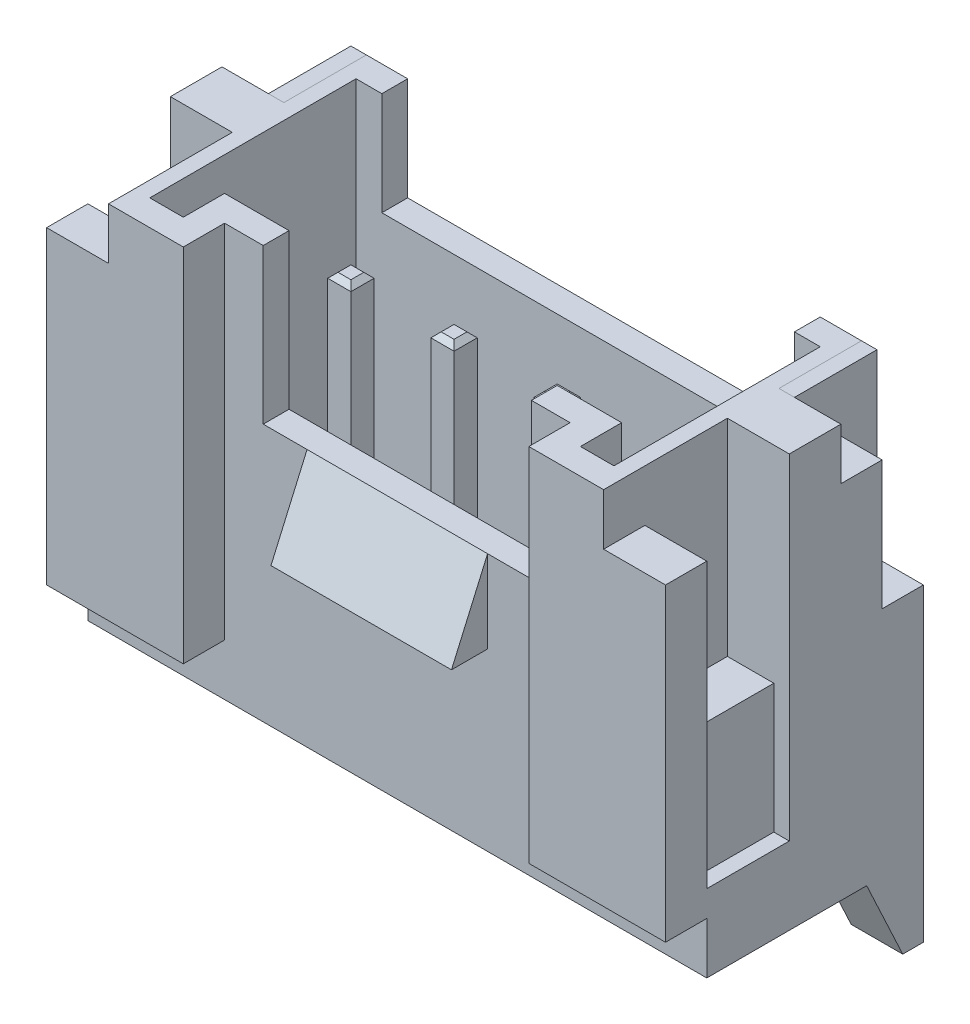
SolidWorks part; units mm, degrees
ref_plane "Plan de face" through (0, 0, 0) normal (0, 0, 1) x (1, 0, 0)
ref_plane "Plan de dessus" through (0, 0, 0) normal (0, 1, 0) x (1, 0, 0)
ref_plane "Plan de droite" through (0, 0, 0) normal (1, 0, 0) x (0, 0, -1)
sketch "Esquisse1" plane through (0, 0, 0) normal (1, 0, 0) x (0, 0, -1)
  line L0 (0, 0) -> (-5, 0)
  line L1 (-5, 0) -> (-5, -7)
  line L2 (-5, -7) -> (-4.2, -7)
  line L3 (-4.2, -7) -> (-4.2, -8)
  line L4 (-4.2, -8) -> (0, -8)
  line L7 (0, -8) -> (0, 0)
  dimension "D1" = 5
  dimension "D2" = 0.8
  dimension "D3" = 1
  dimension "D4" = 8
extrude "Boss.-Extru.1" add sketch "Esquisse1" along normal mid plane 12
sketch "Esquisse2" plane through (0, 0, 0) normal (1, 0, 0) x (0, 0, -1)
  line L0 (0, -8) -> (0, -9.5)
  line L1 (0, -9.5) -> (-0.4, -9.5)
  line L2 (-0.4, -9.5) -> (-1.0995, -8)
  line L3 (-4.2, -8) -> (0, -8) construction
  line L4 (-1.0995, -8) -> (0, -8)
  dimension "D1" = 1.5
  dimension "D2" = 0.4
  dimension "D3" = 25
extrude "Boss.-Extru.2" add sketch "Esquisse2" along normal blind 1 from offset 5
sketch "Esquisse3" plane through (0, 0, 0) normal (0, 1, 0) x (1, 0, 0)
  line L0 (6, -5) -> (-6, -5) construction
  line L1 (3.35, -5.8) -> (-3.35, -5.8)
  line L2 (3.35, -5.8) -> (3.35, -4.2)
  line L3 (3.35, -4.2) -> (-3.35, -4.2)
  line L4 (-3.35, -5.8) -> (-3.35, -4.2)
  line L5 (3.35, -5.8) -> (-3.35, -4.2) construction
  line L6 (3.35, -4.2) -> (-3.35, -5.8) construction
  point P0 (0, -5)
  dimension "D1" = 6.7
  dimension "D2" = 0.8
extrude "Enlèv. mat.-Extru.1" cut sketch "Esquisse3" against normal through all
sketch "Esquisse4" plane through (0, 0, 0) normal (0, 1, 0) x (1, 0, 0)
  line L8 (-6, 0) -> (-6, -5) construction
  line L9 (6, 0) -> (6, -5) construction
  line L16 (-5.5, -4.5) -> (-3.85, -4.5)
  line L17 (-3.85, -4.5) -> (-3.85, -3.7)
  line L18 (-3.85, -3.7) -> (3.85, -3.7)
  line L19 (3.85, -3.7) -> (3.85, -4.5)
  line L20 (3.85, -4.5) -> (5.5, -4.5)
  line L21 (5.5, -4.5) -> (5.5, -0.5)
  line L22 (5.5, -0.5) -> (-5.5, -0.5)
  line L23 (-5.5, -0.5) -> (-5.5, -4.5)
  line L24 (-4.5, -4.5) -> (-3.85, -4.5)
  line L25 (-3.85, -4.5) -> (-3.85, -3.7)
  line L26 (-3.85, -3.7) -> (3.85, -3.7)
  line L27 (3.85, -3.7) -> (3.85, -4.5)
  line L28 (3.85, -4.5) -> (4.5, -4.5)
  line L29 (4.5, -4.5) -> (4.5, -0.5)
  line L30 (4.5, -0.5) -> (-4.5, -0.5)
  line L31 (-4.5, -0.5) -> (-4.5, -4.5)
  dimension "D2" = 1.5
  dimension "D3" = 1.5
  dimension "D1" = 0.5
extrude "Enlèv. mat.-Extru.2" cut sketch "Esquisse4" against normal blind 6.5
sketch "Esquisse7" plane through (6, 0, 0) normal (1, 0, 0) x (0, 0, -1)
  line L0 (-5, -1) -> (-4.2, -1)
  line L1 (-5, 0) -> (-5, -7) construction
  line L2 (-4.2, -1) -> (-4.2, -4)
  line L3 (-4.2, -4) -> (-2.6, -4)
  line L4 (-2.6, -4) -> (-2.6, 0)
  line L5 (0, 0) -> (-5, 0) construction
  line L6 (-2.6, 0) -> (-5, 0)
  line L7 (-5, 0) -> (-5, -1)
  line L8 (0, 0) -> (-1.6, 0)
  line L9 (-1.6, 0) -> (-1.6, -1)
  line L10 (-1.6, -1) -> (-0.8, -1)
  line L11 (-0.8, -1) -> (-0.8, -3.5)
  line L12 (-0.8, -3.5) -> (0, -3.5)
  line L13 (0, -9.5) -> (0, 0) construction
  line L14 (0, -3.5) -> (0, 0)
  dimension "D1" = 1
  dimension "D2" = 2.4
  dimension "D3" = 1.6
  dimension "D4" = 4
  dimension "D5" = 1
  dimension "D6" = 1.8
  dimension "D7" = 3.5
extrude "Enlèv. mat.-Extru.4" cut sketch "Esquisse7" against normal blind 1.2
sketch "Esquisse8" plane through (6, 0, 0) normal (1, 0, 0) x (0, 0, -1)
  line L0 (-2.6, -4) -> (-2.6, 0) construction
  line L1 (-4.2, -4) -> (-2.6, -4)
  line L2 (-4.2, -4) -> (-4.2, -6.5)
  line L3 (-4.2, -6.5) -> (-2.6, -6.5)
  line L4 (-2.6, -4) -> (-2.6, -6.5)
  line L5 (-5, -7) -> (-4.2, -7) construction
  dimension "D1" = 0.5
extrude "Enlèv. mat.-Extru.5" cut sketch "Esquisse8" against normal blind 0.3
sketch "Esquisse9" plane through (0, 0, 0.5) normal (0, 0, 1) x (1, 0, 0)
  line L1 (-2.8, 1) -> (2.8, 1)
  line L2 (-2.8, 1) -> (-2.8, -1)
  line L3 (-2.8, -1) -> (2.8, -1)
  line L4 (2.8, 1) -> (2.8, -1)
  line L5 (-2.8, 1) -> (2.8, -1) construction
  line L6 (-2.8, -1) -> (2.8, 1) construction
  line L7 (4.5, 0) -> (-4.5, 0) construction
  line L8 (4.8, -3.5) -> (4.8, 0) construction
  dimension "D1" = 1
  dimension "D2" = 2
extrude "Enlèv. mat.-Extru.6" cut sketch "Esquisse9" against normal through all
sketch "Esquisse10" plane through (0, 0, 4.2) normal (0, 0, 1) x (1, 0, 0)
  line L1 (-2.6, 3) -> (2.6, 3)
  line L2 (-2.6, 3) -> (-2.6, -3)
  line L3 (-2.6, -3) -> (2.6, -3)
  line L4 (2.6, 3) -> (2.6, -3)
  line L5 (-2.6, 3) -> (2.6, -3) construction
  line L6 (-2.6, -3) -> (2.6, 3) construction
  line L7 (3.35, 0) -> (-3.35, 0) construction
  line L8 (4.8, 0) -> (4.8, -1) construction
  dimension "D1" = 3
  dimension "D2" = 2.2
extrude "Enlèv. mat.-Extru.7" cut sketch "Esquisse10" against normal up to next
sketch "Esquisse12" plane through (0, 0, 0) normal (1, 0, 0) x (0, 0, -1)
  line L0 (-4.2, -3) -> (-4.9, -4.6)
  line L1 (-4.9, -4.6) -> (-4.2, -4.6)
  line L2 (-4.2, -4.6) -> (-4.2, -3)
  dimension "D1" = 0.7
  dimension "D2" = 1.6
extrude "Boss.-Extru.3" add sketch "Esquisse12" along normal mid plane 3.5
sketch "Esquisse5" plane through (0, 0, 0) normal (0, 1, 0) x (1, 0, 0)
  line L0 (4.5, -0.5) -> (2.8, -0.5) construction
  line L1 (4, 0.5) -> (-4, 0.5)
  line L2 (4, 0.5) -> (4, -0.5)
  line L3 (4, -0.5) -> (-4, -0.5)
  line L4 (-4, 0.5) -> (-4, -0.5)
  line L5 (4, 0.5) -> (-4, -0.5) construction
  line L6 (4, -0.5) -> (-4, 0.5) construction
  line L7 (6, -1.6) -> (6, -2.6) construction
  point P0 (0, 0)
  dimension "D1" = 2
extrude "Enlèv. mat.-Extru.3" cut sketch "Esquisse5" against normal blind 2
sketch "Esquisse13" plane through (0, 0, 0) normal (1, 0, 0) x (0, 0, -1)
  line L0 (-2.1, -1.7) -> (-2.1, -8)
  line L1 (-1.85, -8.25) -> (-0.5, -8.25)
  line L2 (-0.25, -8.5) -> (-0.25, -10)
  line L3 (0, -9.5) -> (0, -3.5) construction
  line L4 (-4.2, -8) -> (-1.0995, -8) construction
  arc A0 (-1.85, -8.25) -> (-2.1, -8) centre (-1.85, -8) cw
  arc A1 (-0.5, -8.25) -> (-0.25, -8.5) centre (-0.5, -8.5) cw
  dimension "D1" = 0.25
  dimension "D2" = 0.25
  dimension "D3" = 0.25
  dimension "D4" = 6.3
  dimension "D5" = 2
  dimension "D6" = 2.1
extrude "Extru.-Mince1" add sketch "Esquisse13" along normal mid plane 0.45 from offset 3 separate body thin thin type mid plane wall 0.45
chamfer "Chanfrein1" distance 0.1 angle 45 4 edges at (3, -1.7, 1.875) (3.225, -1.7, 2.1) (3, -1.7, 2.325) (2.775, -1.7, 2.1)
chamfer "Chanfrein2" distance 0.6 distance2 0.3 1 edges at (3, -10, 0.475)
pattern_linear "Répétition linéaire1" count 4 spacing 2 along (-1, 0, 0) of "Extru.-Mince1", "Chanfrein2", "Chanfrein1"
sketch "Esquisse14" plane through (4.8, 0, 0) normal (1, 0, 0) x (0, 0, -1)
  line L6 (0, -3.5) -> (0, 0)
  line L7 (0, 0) -> (-1.6, 0)
  line L8 (-1.6, 0) -> (-1.6, -1)
  line L9 (-1.6, -1) -> (-0.8, -1)
  line L10 (-0.8, -1) -> (-0.8, -3.5)
  line L11 (-0.8, -3.5) -> (0, -3.5)
  line L12 (0, -3.5) -> (0, 0)
  line L13 (0, 0) -> (-1.6, 0)
  line L14 (-1.6, 0) -> (-1.6, -1)
  line L15 (-1.6, -1) -> (-0.8, -1)
  line L16 (-0.8, -1) -> (-0.8, -3.5)
  line L17 (-0.8, -3.5) -> (0, -3.5)
  dimension "D1" = 0
extrude "Boss.-Extru.4" add sketch "Esquisse14" along normal blind 0.3 separate body
mirror "Symétrie2" about plane through (0, 0, 0) normal (1, 0, 0) of "Enlèv. mat.-Extru.5", "Enlèv. mat.-Extru.4", "Boss.-Extru.2"
sketch "Esquisse15" plane through (-4.8, 0, 0) normal (-1, 0, 0) x (0, 0, 1)
  line L6 (0, 0) -> (0, -3.5)
  line L7 (0, -3.5) -> (0.8, -3.5)
  line L8 (0.8, -3.5) -> (0.8, -1)
  line L9 (0.8, -1) -> (1.6, -1)
  line L10 (1.6, -1) -> (1.6, 0)
  line L11 (1.6, 0) -> (0, 0)
  line L12 (0, 0) -> (0, -3.5)
  line L13 (0, -3.5) -> (0.8, -3.5)
  line L14 (0.8, -3.5) -> (0.8, -1)
  line L15 (0.8, -1) -> (1.6, -1)
  line L16 (1.6, -1) -> (1.6, 0)
  line L17 (1.6, 0) -> (0, 0)
  dimension "D1" = 0
extrude "Boss.-Extru.5" add sketch "Esquisse15" along normal blind 0.3 separate body
